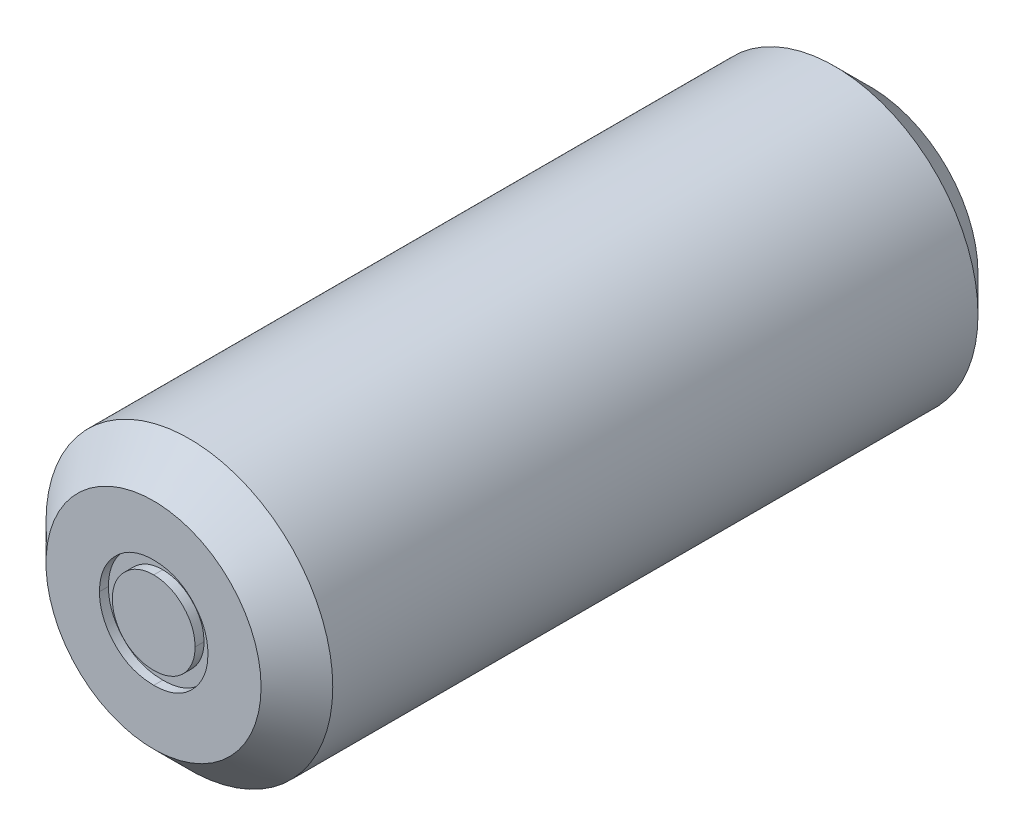
SolidWorks part; units mm, degrees
ref_plane "Front Plane" through (0, 0, 0) normal (1, 0, 0) x (0, 1, 0)
ref_plane "Top Plane" through (0, 0, 0) normal (0, 0, 1) x (0, 1, 0)
ref_plane "Right Plane" through (0, 0, 0) normal (0, 1, 0) x (-1, 0, 0)
sketch "Sketch1" plane through (0, 0, 0) normal (0, 0, 1) x (0, 1, 0)
  circle A0 centre (0, 0) radius 4
  dimension "D1" = 8
extrude "Boss-Extrude1" add sketch "Sketch1" along normal mid plane 20
chamfer "Chamfer1" distance 1 angle 45 2 edges at (4, 0, -10) (4, 0, 10)
sketch "Sketch2" plane through (0, 0, 10) normal (0, 0, 1) x (1, 0, 0)
  text T0 "x" font "Century Gothic" height 4
extrude "Cut-Extrude1" [suppressed] cut sketch "Sketch2" against normal blind 0.25
sketch "Sketch4" plane through (0, 0, 10) normal (0, 0, 1) x (1, 0, 0)
  text T0 "o" font "Century Gothic" height 4
  point P1 (0, 0)
  point P2 (0, 0)
extrude "Cut-Extrude2" cut sketch "Sketch4" against normal blind 0.25
